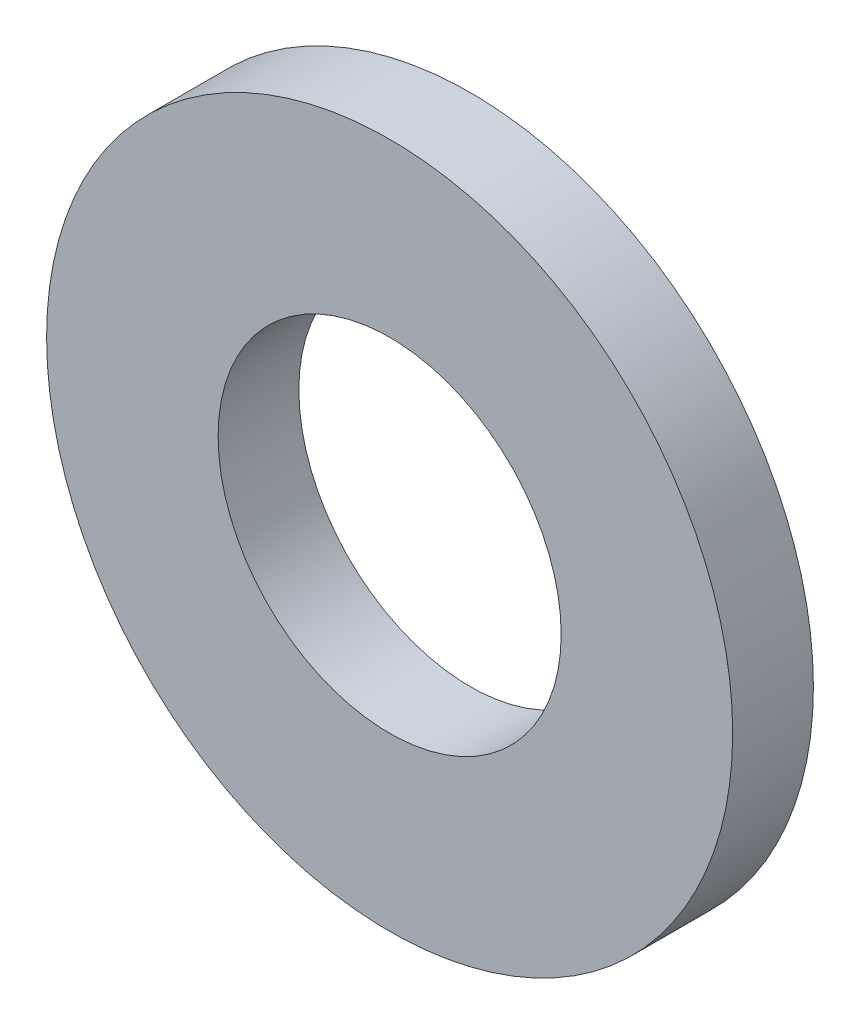
SolidWorks part; units mm, degrees
ref_plane "Front Plane" through (0, 0, 0) normal (0, 0, 1) x (1, 0, 0)
ref_plane "Top Plane" through (0, 0, 0) normal (0, 1, 0) x (1, 0, 0)
ref_plane "Right Plane" through (0, 0, 0) normal (1, 0, 0) x (0, 0, -1)
sketch "Sketch1" plane through (0, 0, 0) normal (0, 0, 1) x (1, 0, 0)
  circle A0 centre (0, 260) radius 4.25
  circle A1 centre (0, 260) radius 8.5
  dimension "D1" = 8.5
  dimension "D2" = 17
extrude "Boss-Extrude1" add sketch "Sketch1" along normal blind 2
